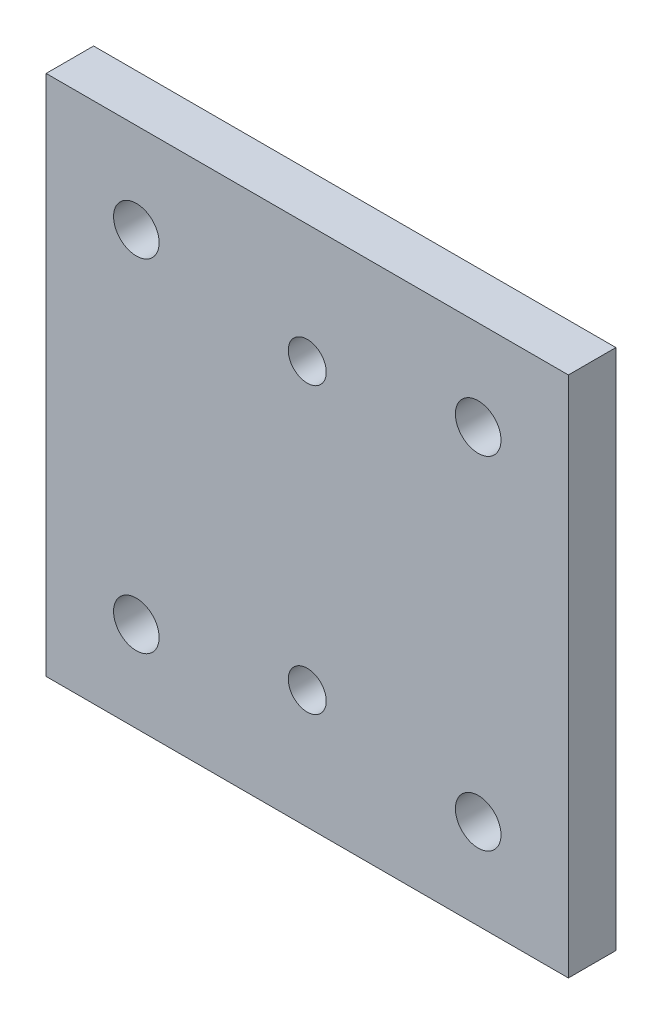
SolidWorks part; units mm, degrees
ref_plane "Front Plane" through (0, 0, 0) normal (0, 0, 1) x (1, 0, 0)
ref_plane "Top Plane" through (0, 0, 0) normal (0, 1, 0) x (1, 0, 0)
ref_plane "Right Plane" through (0, 0, 0) normal (1, 0, 0) x (0, 0, -1)
sketch "Sketch1" plane through (0, 0, 0) normal (0, 0, 1) x (1, 0, 0)
  line L1 (27.5, 27.5) -> (-27.5, 27.5)
  line L2 (27.5, 27.5) -> (27.5, -27.5)
  line L3 (27.5, -27.5) -> (-27.5, -27.5)
  line L4 (-27.5, 27.5) -> (-27.5, -27.5)
  line L5 (27.5, 27.5) -> (-27.5, -27.5) construction
  line L6 (27.5, -27.5) -> (-27.5, 27.5) construction
  point P0 (0, 0)
  dimension "D1" = 55
extrude "Boss-Extrude1" add sketch "Sketch1" along normal mid plane 5
hole_wizard "Ø4.8 (4.8) Diameter Hole1" positions "Sketch2" profile "Sketch3" hole size "Ø4.8" standard "ANSI Metric" end condition up to next
sketch "Sketch2" plane through (0, 0, 2.5) normal (0, 0, 1) x (1, 0, 0)
  line L0 (27.5, 27.5) -> (-27.5, 27.5) construction
  line L1 (27.5, -27.5) -> (27.5, 27.5) construction
  point P0 (18, 18)
  dimension "D1" = 9.5
  dimension "D2" = 9.5
sketch "Sketch3" plane through (18, 18, 2.5) normal (1, 0, 0) x (0, -1, 0)
  line L0 (0, 0) -> (0, 5)
  line L1 (0, 5) -> (2.4, 5)
  line L2 (2.4, 5) -> (2.4, 0)
  line L5 (2.4, 0) -> (0, 0)
  line L11 (0, -6.35) -> (0, 107.95) construction
  dimension "Thru Hole Dia." = 4.8
  dimension "Thru Hole Depth" = 5
pattern_linear "LPattern1" count 2 spacing 36 along (-1, 0, 0) count 2 spacing 36 along (0, -1, 0) of "Ø4.8 (4.8) Diameter Hole1"
sketch "Sketch4" plane through (0, 0, 2.5) normal (0, 0, 1) x (1, 0, 0)
  line L0 (0, -15) -> (0, 15) construction
  circle A0 centre (0, 15) radius 2
  circle A1 centre (0, -15) radius 2
  dimension "D3" = 4
  dimension "D1" = 15
  dimension "D2" = 30
extrude "Cut-Extrude1" cut sketch "Sketch4" against normal through all
